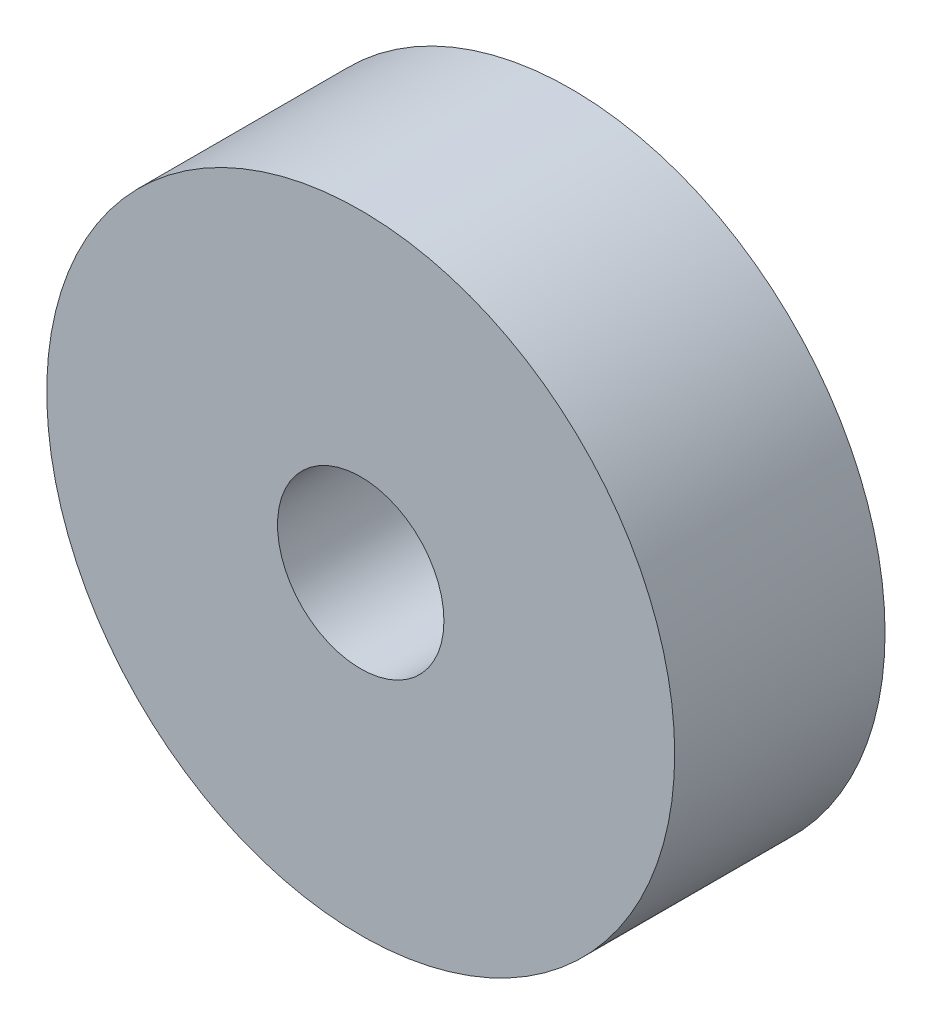
SolidWorks part; units mm, degrees
ref_plane "Piano frontale" through (0, 0, 0) normal (0, 0, 1) x (1, 0, 0)
ref_plane "Piano superiore" through (0, 0, 0) normal (0, 1, 0) x (1, 0, 0)
ref_plane "Piano destro" through (0, 0, 0) normal (1, 0, 0) x (0, 0, -1)
sketch "Schizzo1" plane through (0, 0, 0) normal (0, 0, 1) x (1, 0, 0)
  circle A0 centre (0, 0) radius 100
  circle A1 centre (0, 0) radius 26.5
  dimension "D1" = 200
  dimension "D2" = 53
extrude "Estrusione-Estrusione1" add sketch "Schizzo1" along normal blind 67
